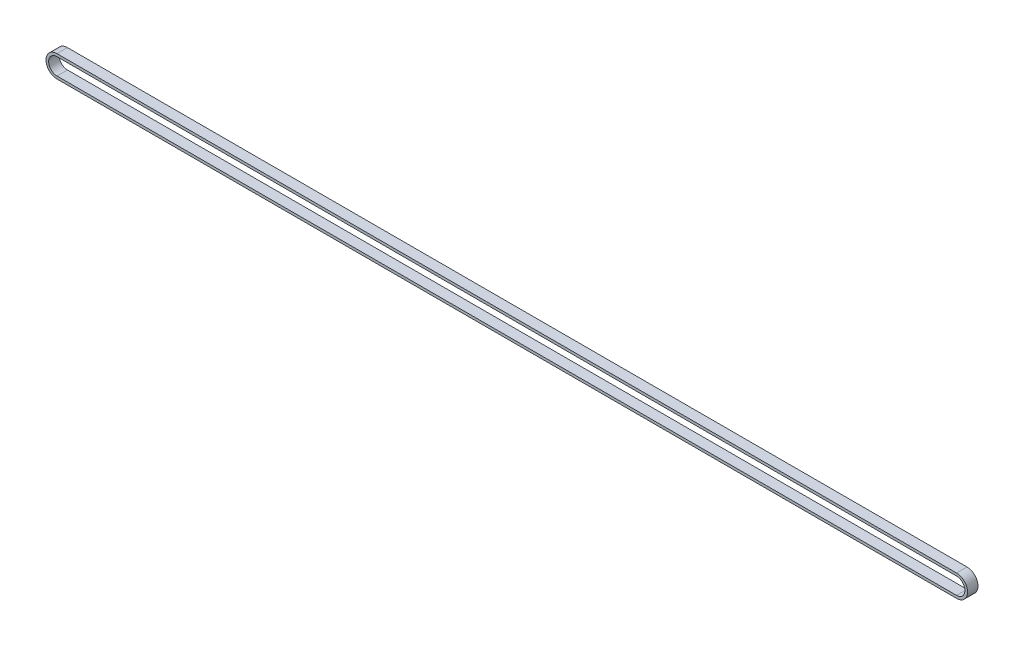
SolidWorks part; units mm, degrees
ref_plane "Ön Düzlem" through (0, 0, 0) normal (0, 0, 1) x (1, 0, 0)
ref_plane "Üst Düzlem" through (0, 0, 0) normal (0, 1, 0) x (1, 0, 0)
ref_plane "Sağ Düzlem" through (0, 0, 0) normal (1, 0, 0) x (0, 0, -1)
sketch "Sketch1" plane through (0, 0, 0) normal (0, 0, 1) x (1, 0, 0)
  line L0 (-257.75, 0.2357) -> (257.75, 0.2357)
  line L1 (-257.75, -10.8643) -> (257.75, -10.8643)
  line L3 (-257.75, -1.2643) -> (257.75, -1.2643)
  line L5 (-257.75, -12.3643) -> (257.75, -12.3643)
  line L6 (0, 40.9776) -> (0, -35.1687) construction
  arc A0 (-257.75, -1.2643) -> (-257.75, -10.8643) centre (-257.75, -6.0643) ccw
  arc A2 (257.75, -10.8643) -> (257.75, -1.2643) centre (257.75, -6.0643) ccw
  arc A3 (257.75, -12.3643) -> (257.75, 0.2357) centre (257.75, -6.0643) ccw
  arc A4 (-257.75, 0.2357) -> (-257.75, -12.3643) centre (-257.75, -6.0643) ccw
  point P0 (0, 0)
  dimension "D2" = 4.8
  dimension "D3" = 4.8
  dimension "D4" = 257.75
  dimension "D5" = 257.75
  dimension "D1" = 1.5
extrude "Boss-Extrude1" add sketch "Sketch1" along normal blind 6
